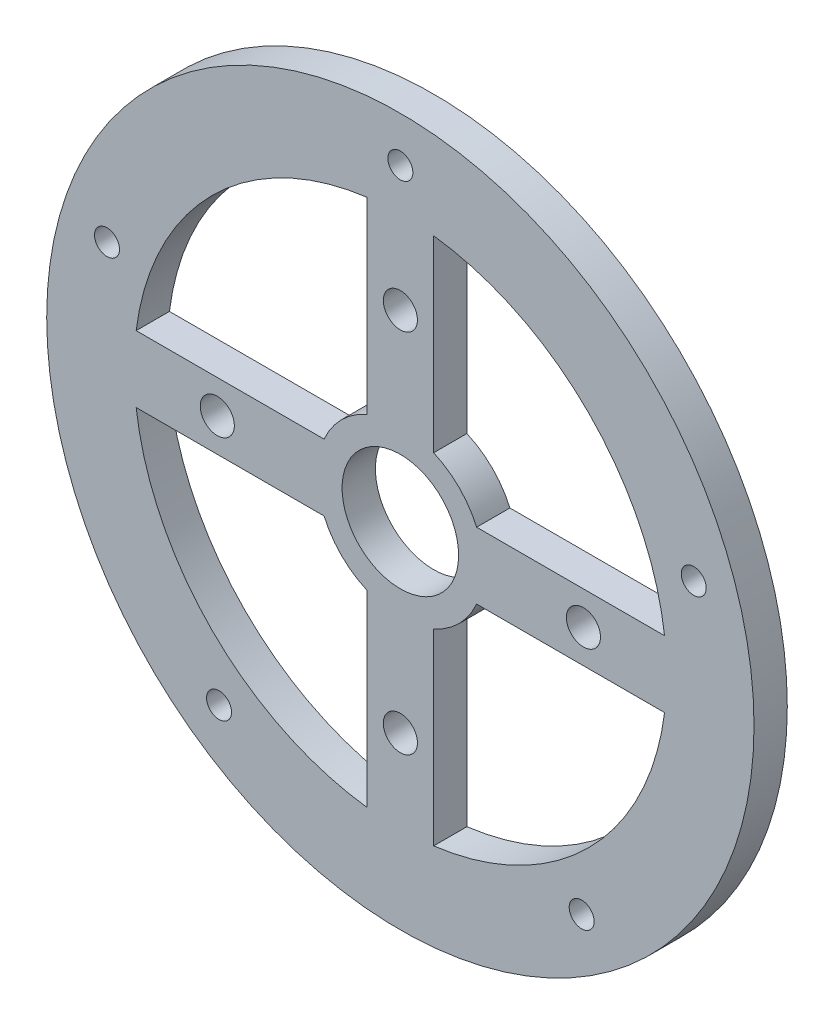
SolidWorks part; units mm, degrees
ref_plane "Front Plane" through (0, 0, 0) normal (0, 0, 1) x (1, 0, 0)
ref_plane "Top Plane" through (0, 0, 0) normal (0, 1, 0) x (1, 0, 0)
ref_plane "Right Plane" through (0, 0, 0) normal (1, 0, 0) x (0, 0, -1)
sketch "Sketch1" plane through (0, 0, 0) normal (0, 0, 1) x (1, 0, 0)
  circle A0 centre (0, 0) radius 42.5
  circle A1 centre (0, 0) radius 32
  circle A2 centre (0, 37.0667) radius 1.5
  circle A3 centre (35.2525, 11.4542) radius 1.5
  circle A4 centre (21.7872, -29.9876) radius 1.5
  circle A5 centre (-21.7872, -29.9876) radius 1.5
  circle A6 centre (-35.2525, 11.4542) radius 1.5
  point P16 (0, 0)
  dimension "D1" = 85
  dimension "D2" = 64
  dimension "D3" = 3
  dimension "D4" = 5
extrude "Boss-Extrude1" add sketch "Sketch1" along normal blind 4
sketch "Sketch2" plane through (0, 0, 4) normal (0, 0, 1) x (1, 0, 0)
  line L12 (-9.1652, 4) -> (-31.749, 4)
  line L16 (-9.1652, -4) -> (-31.749, -4)
  line L18 (-4, -9.1652) -> (-4, -31.749)
  line L20 (0, -19.95) -> (0, -32)
  line L22 (4, -9.1652) -> (4, -31.749)
  line L24 (9.1652, -4) -> (31.749, -4)
  line L28 (9.1652, 4) -> (31.749, 4)
  line L30 (4, 9.1652) -> (4, 31.749)
  line L32 (0, 19.95) -> (0, 32)
  line L34 (-4, 9.1652) -> (-4, 31.749)
  circle A0 centre (0, 0) radius 22 construction
  circle A1 centre (0, 22) radius 2.05
  circle A2 centre (22, 0) radius 2.05
  circle A3 centre (0, -22) radius 2.05
  circle A4 centre (-22, 0) radius 2.05
  arc A5 (-4, 9.1652) -> (-9.1652, 4) centre (0, 0) ccw
  circle A6 centre (0, 0) radius 32 construction
  arc A7 (9.1652, 4) -> (4, 9.1652) centre (0, 0) ccw
  arc A8 (4, -9.1652) -> (9.1652, -4) centre (0, 0) ccw
  arc A9 (-9.1652, -4) -> (-4, -9.1652) centre (0, 0) ccw
  arc A10 (-31.749, 4) -> (-31.749, -4) centre (0, 0) ccw
  arc A11 (-4, -31.749) -> (4, -31.749) centre (0, 0) ccw
  arc A12 (31.749, -4) -> (31.749, 4) centre (0, 0) ccw
  arc A13 (4, 31.749) -> (-4, 31.749) centre (0, 0) ccw
  circle A14 centre (0, 0) radius 7
  point P14 (0, 0)
  dimension "D1" = 44
  dimension "D2" = 4.1
  dimension "D4" = 20
  dimension "D5" = 14
  dimension "D3" = 4
extrude "Boss-Extrude2" add sketch "Sketch2" against normal through all
